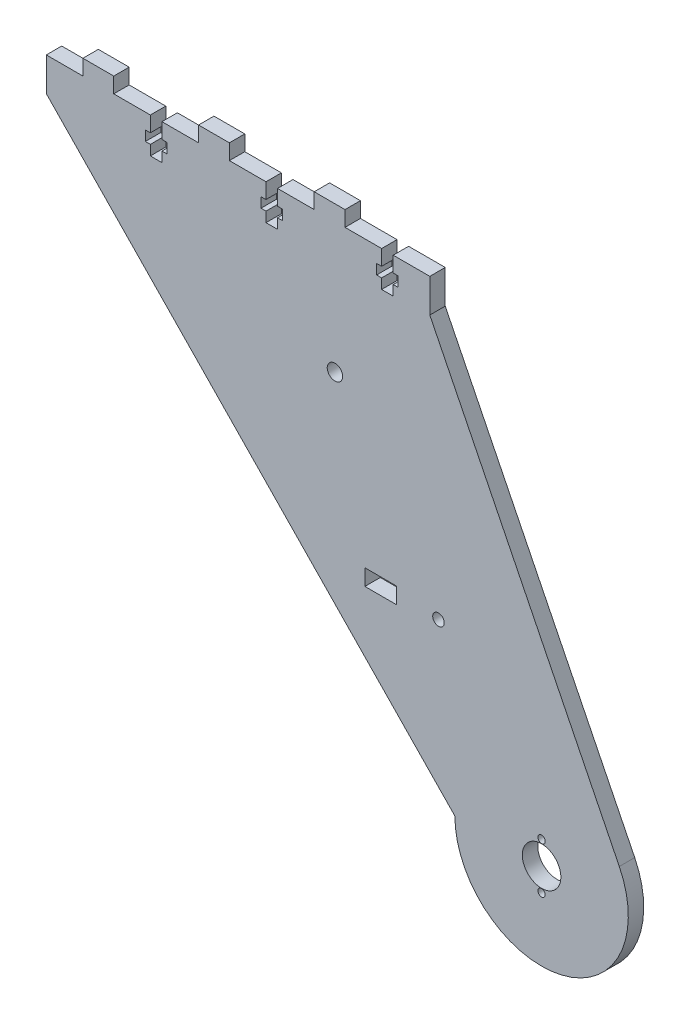
SolidWorks part; units mm, degrees
ref_plane "前视基准面" through (0, 0, 0) normal (0, 0, 1) x (1, 0, 0)
ref_plane "上视基准面" through (0, 0, 0) normal (0, 1, 0) x (1, 0, 0)
ref_plane "右视基准面" through (0, 0, 0) normal (1, 0, 0) x (0, 0, -1)
sketch "草图1" plane through (0, 0, 0) normal (0, 0, 1) x (1, 0, 0)
  line L0 (33.35, -51.75) -> (-20.2627, 32.422) construction
  line L1 (-20.2627, 32.422) -> (-36.65, 58.15) construction
  line L2 (-36.65, 68.25) -> (-36.65, 58.15) construction
  line L15 (-38.15, 66.25) -> (-38.15, 62.25)
  line L16 (-38.15, 62.25) -> (-39.45, 62.25)
  line L17 (-39.45, 62.25) -> (-39.45, 59.65)
  line L18 (-39.45, 59.65) -> (-38.15, 59.65)
  line L19 (-38.15, 59.65) -> (-38.15, 57.05)
  line L20 (-38.15, 57.05) -> (-35.15, 57.05)
  line L21 (-38.15, 66.25) -> (-47.65, 66.25)
  line L22 (-51.65, 66.25) -> (-51.65, 70.25) construction
  line L23 (-47.65, 66.25) -> (-55.65, 66.25) construction
  line L24 (-47.65, 66.25) -> (-47.65, 70.25)
  line L25 (-47.65, 70.25) -> (-55.65, 70.25)
  line L26 (-55.65, 66.25) -> (-55.65, 70.25)
  line L27 (-25.65, 66.25) -> (-17.65, 66.25) construction
  line L28 (-21.65, 66.25) -> (-21.65, 70.25) construction
  line L29 (-17.65, 66.25) -> (-17.65, 70.25)
  line L30 (-25.65, 70.25) -> (-17.65, 70.25)
  line L31 (-25.65, 66.25) -> (-25.65, 70.25)
  line L32 (-35.15, 66.25) -> (-25.65, 66.25)
  line L33 (-35.15, 59.65) -> (-35.15, 57.05)
  line L34 (-33.85, 59.65) -> (-35.15, 59.65)
  line L35 (-33.85, 62.25) -> (-33.85, 59.65)
  line L36 (-35.15, 62.25) -> (-33.85, 62.25)
  line L37 (-35.15, 66.25) -> (-35.15, 62.25)
  line L38 (-95.15, 66.25) -> (-95.15, 57.55)
  line L39 (-95.15, 57.55) -> (10.85, -51.75)
  line L40 (-68.15, 66.25) -> (-68.15, 62.25)
  line L41 (-68.15, 62.25) -> (-69.45, 62.25)
  line L42 (-69.45, 62.25) -> (-69.45, 59.65)
  line L43 (-69.45, 59.65) -> (-68.15, 59.65)
  line L44 (-68.15, 59.65) -> (-68.15, 57.05)
  line L45 (-68.15, 66.25) -> (-77.65, 66.25)
  line L46 (-6.65, 68.25) -> (-6.65, 58.15) construction
  line L49 (-65.15, 57.05) -> (-68.15, 57.05)
  line L50 (-65.15, 59.65) -> (-65.15, 57.05)
  line L51 (-63.85, 59.65) -> (-65.15, 59.65)
  line L52 (-63.85, 62.25) -> (-63.85, 59.65)
  line L53 (-65.15, 62.25) -> (-63.85, 62.25)
  line L54 (-65.15, 66.25) -> (-65.15, 62.25)
  line L55 (-55.65, 66.25) -> (-65.15, 66.25)
  line L58 (-8.15, 66.25) -> (-17.65, 66.25)
  line L59 (-95.15, 66.25) -> (-85.65, 66.25)
  line L60 (-85.65, 66.25) -> (-85.65, 70.25)
  line L61 (-77.65, 70.25) -> (-85.65, 70.25)
  line L62 (-77.65, 66.25) -> (-77.65, 70.25)
  line L63 (4.35, 66.25) -> (4.35, 57.55)
  line L65 (6.5984, -9.75) -> (-8.4016, -9.75) construction
  line L66 (-8.15, 66.25) -> (-8.15, 62.25)
  line L67 (-8.15, 62.25) -> (-9.45, 62.25)
  line L68 (-9.45, 62.25) -> (-9.45, 59.65)
  line L69 (-9.45, 59.65) -> (-8.15, 59.65)
  line L70 (-8.15, 59.65) -> (-8.15, 57.05)
  line L74 (-5.15, 66.25) -> (4.35, 66.25)
  line L75 (-5.15, 57.05) -> (-8.15, 57.05)
  line L76 (-5.15, 59.65) -> (-5.15, 57.05)
  line L77 (-3.85, 59.65) -> (-5.15, 59.65)
  line L78 (-3.85, 62.25) -> (-3.85, 59.65)
  line L79 (-5.15, 62.25) -> (-3.85, 62.25)
  line L80 (-5.15, 66.25) -> (-5.15, 62.25)
  line L86 (4.35, 57.55) -> (53.5146, -41.7681)
  line L87 (-12.5016, -11.85) -> (-4.3016, -11.85)
  line L88 (-12.5016, -11.85) -> (-12.5016, -7.65)
  line L89 (-12.5016, -7.65) -> (-4.3016, -7.65)
  line L90 (-4.3016, -11.85) -> (-4.3016, -7.65)
  line L91 (-12.5016, -11.85) -> (-4.3016, -7.65) construction
  line L92 (-12.5016, -7.65) -> (-4.3016, -11.85) construction
  circle A0 centre (-36.65, 68.25) radius 1.5 construction
  circle A1 centre (-20.2627, 32.422) radius 2
  circle A2 centre (6.5984, -9.75) radius 1.5
  circle A3 centre (33.35, -51.75) radius 22.5 construction
  arc A6 (10.85, -51.75) -> (53.5146, -41.7681) centre (33.35, -51.75) ccw
  circle A7 centre (33.35, -51.75) radius 5
  circle A8 centre (33.35, -51.75) radius 6 construction
  circle A9 centre (33.35, -45.75) radius 0.95
  circle A10 centre (33.35, -57.75) radius 0.95
  point P39 (-36.65, 57.05)
  point P61 (-66.65, 57.05)
  point P91 (-6.65, 57.05)
  dimension "D17" = 10
  dimension "D1" = 120
  dimension "D2" = 70
  dimension "D3" = 42
  dimension "D4" = 50
  dimension "D5" = 4
  dimension "D6" = 2
  dimension "D7" = 2.6
  dimension "D8" = 2.6
  dimension "D9" = 9.5
  dimension "D10" = 8
  dimension "D11" = 4
  dimension "D12" = 5.6
  dimension "D13" = 8.2
  dimension "D14" = 4.2
  dimension "D15" = 10.1
  dimension "D16" = 15
extrude "凸台-拉伸1" add sketch "草图1" along normal blind 4
sketch "草图2" plane through (0, 66.25, 0) normal (0, 1, 0) x (1, 0, 0)
  line L0 (-68.15, -2) -> (-65.15, -2)
  line L1 (-68.15, -4) -> (-68.15, 0) construction
  line L2 (-65.15, -4) -> (-65.15, 0) construction
  circle A0 centre (-66.65, -2) radius 1.5
